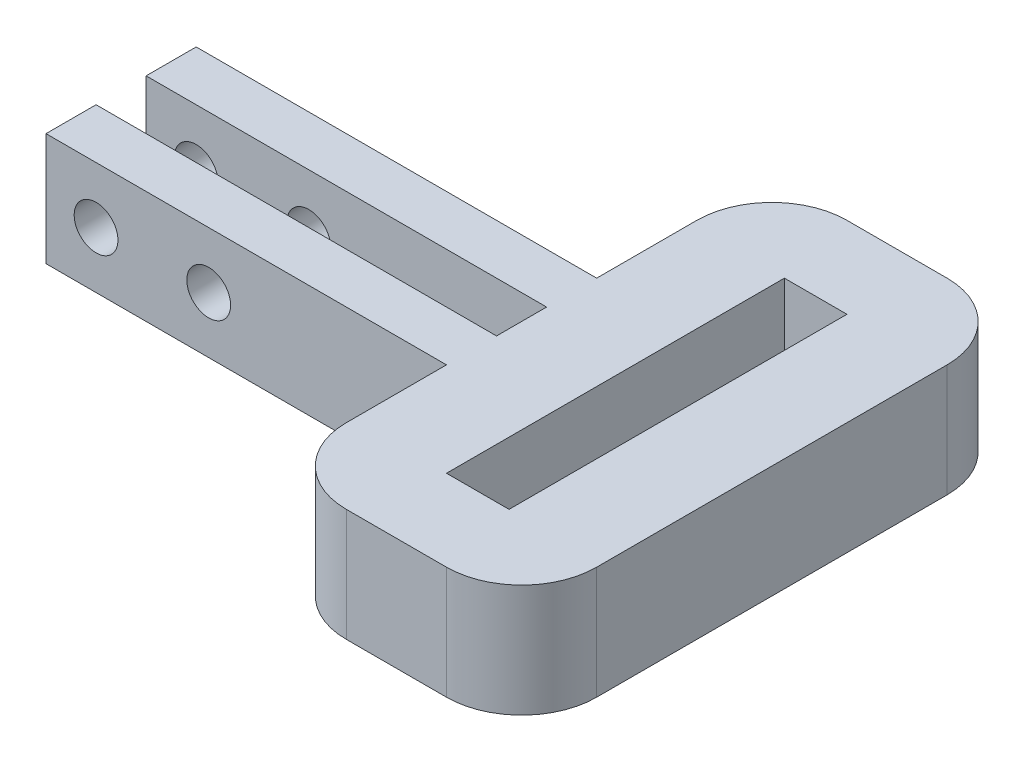
SolidWorks part; units mm, degrees
ref_plane "Front" through (0, 0, 0) normal (0, 0, 1) x (1, 0, 0)
ref_plane "Top" through (0, 0, 0) normal (0, 1, 0) x (1, 0, 0)
ref_plane "Right" through (0, 0, 0) normal (1, 0, 0) x (0, 0, -1)
sketch "Croquis1" plane through (0, 0, 0) normal (0, 1, 0) x (1, 0, 0)
  line L0 (-223.043, 0) -> (10929.1056, 0) construction
  line L1 (0, -223.043) -> (0, 10929.1056) construction
  line L2 (-223.043, -2.5) -> (10929.1056, -2.5) construction
  line L3 (-2, -10) -> (2, -10)
  line L4 (-5, -992.5198) -> (-5, 49007.4802) construction
  line L5 (-2, 10) -> (2, 10)
  line L6 (5, 7) -> (5, -7)
  line L7 (-5, -10) -> (5, 10) construction
  line L8 (-5, 10) -> (5, -10) construction
  line L9 (-223.043, 2.5) -> (10929.1056, 2.5) construction
  line L10 (-21, 1) -> (-21, 3)
  line L11 (-1.25, -6.75) -> (1.25, -6.75)
  line L12 (-1.25, -6.75) -> (-1.25, 6.75)
  line L13 (-1.25, 6.75) -> (1.25, 6.75)
  line L14 (1.25, -6.75) -> (1.25, 6.75)
  line L15 (-1.25, -6.75) -> (1.25, 6.75) construction
  line L16 (-1.25, 6.75) -> (1.25, -6.75) construction
  line L17 (-21, 3) -> (-5, 3)
  line L18 (-21, 1) -> (-5, 1)
  line L19 (-5, 1) -> (-5, -1)
  line L20 (-5, -1) -> (-21, -1)
  line L21 (-5, 3) -> (-5, 7)
  line L22 (-5, -3) -> (-5, -7)
  line L23 (-21, -3) -> (-5, -3)
  line L24 (-21, -1) -> (-21, -3)
  arc A0 (-5, 7) -> (-2, 10) centre (-2, 7) cw
  arc A1 (-2, -10) -> (-5, -7) centre (-2, -7) cw
  arc A2 (5, 7) -> (2, 10) centre (2, 7) ccw
  arc A3 (5, -7) -> (2, -10) centre (2, -7) cw
  point P4 (0, 0)
  point P22 (0, 0)
  point P32 (0.6, 0)
  dimension "D3" = 16
  dimension "D5" = 3
  dimension "D6" = 3
  dimension "D7" = 13.5
  dimension "D8" = 2.5
  dimension "D1" = 20
  dimension "D2" = 10
  dimension "D11" = 14
  dimension "D12" = 2
  dimension "D13" = 1
  dimension "D9" = 2.5
  dimension "D10" = 2.5
extrude "Saliente-Extruir1" add sketch "Croquis1" along normal blind 4.5
ref_plane "Plano1" through (0, 0, 1.5) normal (0, 0, 1) x (1, 0, 0)
sketch "Croquis7" plane through (0, 0, 3) normal (0, 0, 1) x (1, 0, 0)
  line L0 (-1000, 0) -> (49000, 0) construction
  line L1 (-1000.1155, 2.25) -> (48999.8845, 2.25) construction
  line L2 (0, -1000) -> (0, 49000) construction
  line L3 (-21, 4.5) -> (-21, 0) construction
  circle A0 centre (-19, 2.25) radius 0.875
  circle A2 centre (-14.5, 2.25) radius 0.875
  dimension "D2" = 2
  dimension "D3" = 1.75
  dimension "D4" = 1.75
  dimension "D5" = 4.5
  dimension "D1" = 2.25
extrude "Cortar-Extruir4" cut sketch "Croquis7" against normal through all and the other way blind 10
sketch "Croquis2" plane through (0, 4.5, 0) normal (0, 1, 0) x (1, 0, 0)
  line L0 (0, -1000) -> (0, 49000) construction
  line L1 (-1000, 0) -> (49000, 0) construction
  line L2 (-1000, -6.5) -> (49000, -6.5) construction
  line L3 (-1000, 6.5) -> (49000, 6.5) construction
  line L4 (5, -1000) -> (5, 49000) construction
  line L5 (-7, -1000) -> (-7, 49000) construction
  line L6 (-5, 6.5) -> (-1.5, 6.5)
  line L7 (-1.5, 6.5) -> (-1.5, 4.5)
  line L8 (-1.5, 4.5) -> (-5, 4.5)
  line L9 (-5, 4.5) -> (-5, 6.5)
  line L10 (-5, -4.5) -> (-5, -6.5)
  line L11 (-1.5, -4.5) -> (-5, -4.5)
  line L12 (-1.5, -6.5) -> (-1.5, -4.5)
  line L13 (-5, -6.5) -> (-1.5, -6.5)
  line L14 (5, -4.5) -> (5, -6.5)
  line L15 (5, -6.5) -> (1.5, -6.5)
  line L16 (1.5, -6.5) -> (1.5, -4.5)
  line L17 (1.5, -4.5) -> (5, -4.5)
  point P16 (-3.25, 6.5)
  dimension "D5" = 3.5
  dimension "D6" = 2
  dimension "D7" = 1.5
  dimension "D1" = 6.5
  dimension "D2" = 6.5
  dimension "D3" = 5
extrude "Saliente-Extruir2" [suppressed] add sketch "Croquis2" along normal blind 9
sketch "Croquis3" [suppressed] plane through (0, 0, 6.5) normal (0, 0, 1) x (1, 0, 0)
  line L2 (0, -1000) -> (0, 49000) construction
  line L3 (1.5, 12) -> (5, 12) construction
  line L5 (1.5, 12) -> (1.5, 3) construction
  circle A1 centre (3.5, 10) radius 1.125
  dimension "D1" = 2
  dimension "D2" = 2
extrude "Cortar-Extruir1" [suppressed] cut sketch "Croquis3" against normal up to surface (13 mm away)
sketch "Croquis4" [suppressed] plane through (0, 0, 6.5) normal (0, 0, 1) x (1, 0, 0)
  line L0 (-3.25, -993) -> (-3.25, 49007) construction
  line L1 (-5, 12) -> (-1.5, 12) construction
  line L2 (-1007.7153, 10.45) -> (48992.2847, 10.45) construction
  line L4 (-1.5, 12) -> (-1.5, 3) construction
  line L5 (-5, 12) -> (-1.5, 12)
  line L6 (-5, 12) -> (-5, 10.45)
  line L7 (-5, 10.45) -> (-1.5, 10.45)
  line L8 (-1.5, 12) -> (-1.5, 10.45)
  point P5 (-3.25, 12)
  dimension "D1" = 1.55
extrude "Cortar-Extruir2" [suppressed] cut sketch "Croquis4" against normal up to surface (13 mm away)
fillet "Redondeo1" [suppressed] radius 2
sketch "Croquis5" [suppressed] plane through (-5, 0, 0) normal (-1, 0, 0) x (0, 0, 1)
  line L0 (6.5, 12) -> (6.5, 3) construction
  line L1 (4.5, 12) -> (6.5, 12)
  line L2 (4.5, 12) -> (4.5, 8)
  line L3 (4.5, 8) -> (6.5, 8)
  line L4 (6.5, 12) -> (6.5, 8)
  line L5 (0, -1000) -> (0, 49000) construction
  line L6 (-7, 0) -> (7, 0) construction
  line L7 (-4.5, 12) -> (-4.5, 8)
  line L8 (-4.5, 8) -> (-6.5, 8)
  line L9 (-6.5, 12) -> (-6.5, 8)
  line L10 (-4.5, 12) -> (-6.5, 12)
  point P12 (0, 0)
  dimension "D1" = 4
extrude "Saliente-Extruir3" [suppressed] add sketch "Croquis5" along normal blind 4
sketch "Croquis6" [suppressed] plane through (0, 0, 6.5) normal (0, 0, 1) x (1, 0, 0)
  line L0 (-5, 8) -> (-9, 12) construction
  line L1 (-9, 8) -> (-5.25, 12) construction
  line L2 (-9, 12) -> (-1.5, 12) construction
  circle A0 centre (-7, 10) radius 1.125
  dimension "D1" = 2.25
extrude "Cortar-Extruir3" [suppressed] cut sketch "Croquis6" against normal through all
fillet "Redondeo2" [suppressed] radius 1
